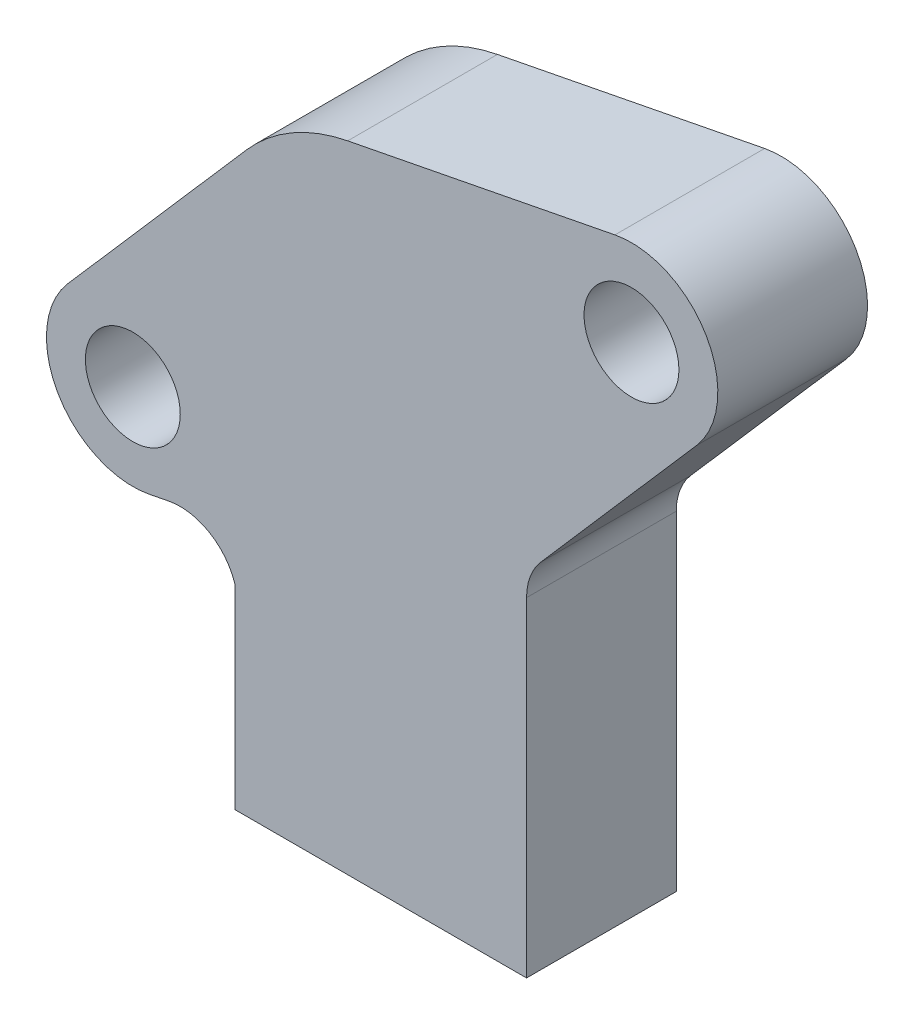
SolidWorks part; units mm, degrees
ref_plane "Front Plane" through (0, 0, 0) normal (0, 0, 1) x (1, 0, 0)
ref_plane "Top Plane" through (0, 0, 0) normal (0, 1, 0) x (1, 0, 0)
ref_plane "Right Plane" through (0, 0, 0) normal (1, 0, 0) x (0, 0, -1)
sketch "Sketch1" plane through (0, 0, 2.1073) normal (0, 0, 1) x (1, 0, 0)
  line L0 (13.3239, 2.6619) -> (0.6739, 2.6619) construction
  line L1 (0.6739, 2.6619) -> (0.6739, -2.4381) construction
  line L2 (0.6739, -2.4381) -> (13.3239, -2.4381) construction
  line L3 (13.3239, -2.4381) -> (13.3239, 2.6619) construction
  line L4 (13.6414, 2.9794) -> (0.3564, 2.9794)
  line L5 (0.3564, 2.9794) -> (0.3564, -2.7556)
  line L6 (0.3564, -2.7556) -> (13.6414, -2.7556)
  line L7 (-0.9761, 8.4284) -> (0.2939, 8.4284)
  line L8 (15.8915, 15.0877) -> (24.488, 24.9606)
  line L9 (19.9838, 32.7623) -> (5.2476, 29.8855)
  line L10 (-0.3323, 26.6639) -> (-10.1918, 15.3404)
  line L11 (-5.6875, 7.5388) -> (-4.5981, 7.7515)
  line L12 (-0.9761, 8.4284) -> (0.2939, 8.4284)
  line L13 (0.2939, 8.4284) -> (0.2939, 9.933)
  line L15 (15.8915, 15.0877) -> (24.488, 24.9606)
  line L16 (19.9838, 32.7623) -> (5.2476, 29.8855)
  line L17 (-0.3323, 26.6639) -> (-10.1918, 15.3404)
  line L18 (-5.6875, 7.5388) -> (-4.5981, 7.7515)
  line L21 (13.6414, -2.7556) -> (13.6414, 2.9794)
  line L44 (0.2939, 8.4284) -> (0.2939, 9.933)
  line L45 (-0.8698, 15.2437) -> (-0.9761, 15.4746)
  line L46 (-0.8698, 15.2437) -> (-0.9761, 15.4746)
  line L47 (15.111, 16.1833) -> (14.5824, 14.7049)
  line L48 (15.111, 16.1833) -> (14.5824, 14.7049)
  line L49 (13.841, 10.4291) -> (13.841, 8.4284)
  line L50 (13.841, 10.4291) -> (13.841, 8.4284)
  line L51 (13.841, 8.4284) -> (15.111, 8.4284)
  line L52 (13.841, 8.4284) -> (15.111, 8.4284)
  line L53 (15.111, 8.4284) -> (15.111, 13.0027)
  line L54 (15.111, 8.4284) -> (15.111, 13.0027)
  circle A0 centre (-6.6, 12.213) radius 2.6162 construction
  circle A1 centre (20.8963, 28.088) radius 2.6162 construction
  circle A2 centre (-6.6, 12.213) radius 2.6162
  circle A3 centre (20.8963, 28.088) radius 2.6162
  arc A5 (15.8915, 15.0877) -> (15.111, 13.0027) centre (18.286, 13.0027) ccw
  arc A6 (24.488, 24.9606) -> (19.9838, 32.7623) centre (20.8963, 28.088) ccw
  arc A7 (5.2476, 29.8855) -> (-0.3323, 26.6639) centre (7.1481, 20.1505) ccw
  arc A8 (-10.1918, 15.3404) -> (-5.6875, 7.5388) centre (-6.6, 12.213) ccw
  arc A9 (-0.9761, 8.4284) -> (-4.5981, 7.7515) centre (-0.9761, -1.5994) ccw
  arc A10 (15.8915, 15.0877) -> (15.111, 13.0027) centre (18.286, 13.0027) ccw
  arc A11 (24.488, 24.9606) -> (19.9838, 32.7623) centre (20.8963, 28.088) ccw
  arc A12 (5.2476, 29.8855) -> (-0.3323, 26.6639) centre (7.1481, 20.1505) ccw
  arc A13 (-10.1918, 15.3404) -> (-5.6875, 7.5388) centre (-6.6, 12.213) ccw
  arc A30 (-0.9761, 8.4284) -> (-4.5981, 7.7515) centre (-0.9761, -1.5994) ccw
  arc A31 (0.2939, 9.933) -> (-0.8698, 15.2437) centre (-12.4061, 9.933) ccw
  arc A32 (0.2939, 9.933) -> (-0.8698, 15.2437) centre (-12.4061, 9.933) ccw
  arc A33 (15.111, 16.1833) -> (-0.9761, 15.4746) centre (6.9229, 19.1109) ccw
  arc A34 (15.111, 16.1833) -> (-0.9761, 15.4746) centre (6.9229, 19.1109) ccw
  arc A35 (14.5824, 14.7049) -> (13.841, 10.4291) centre (26.541, 10.4291) ccw
  arc A36 (14.5824, 14.7049) -> (13.841, 10.4291) centre (26.541, 10.4291) ccw
  dimension "D1" = 0
  dimension "D2" = 0.3175
extrude "Boss-Extrude1" add sketch "Sketch1" along normal blind 8.255
sketch "Sketch2" plane through (0, 0, 10.3623) normal (0, 0, 1) x (1, 0, 0)
  line L0 (0.2939, 2.9794) -> (13.841, 2.9794)
  line L1 (0.6739, 2.6619) -> (13.3239, 2.6619) construction
  line L2 (-0.9761, 2.9039) -> (-0.9761, 5.6344) construction
  line L3 (-0.9761, 2.9039) -> (-0.9761, 5.6344)
  line L4 (0.2939, 8.4284) -> (0.2939, 2.9794)
  line L5 (13.841, 10.4291) -> (13.841, 8.4284)
  line L8 (-0.8698, 15.2437) -> (-0.9761, 15.4746)
  line L9 (15.111, 16.1833) -> (14.5824, 14.7049)
  line L10 (13.841, 2.9794) -> (13.841, 8.4284)
  line L13 (-0.8698, 15.2437) -> (-0.9761, 15.4746)
  line L14 (15.111, 16.1833) -> (14.5824, 14.7049)
  line L15 (15.111, 8.4284) -> (15.111, 2.9039)
  line L16 (0.2939, 2.9039) -> (0.2939, 2.9794)
  line L17 (13.841, 2.9039) -> (13.841, 2.9794)
  line L20 (0.2939, 2.9039) -> (-0.9761, 2.9039)
  line L21 (-0.9761, 2.9039) -> (-0.9761, -5.1606)
  line L22 (-0.9761, -5.1606) -> (15.111, -5.1606)
  line L23 (-5.6875, 7.5388) -> (-4.5981, 7.7515)
  line L24 (-5.6875, 7.5388) -> (-4.5981, 7.7515)
  line L25 (-0.9761, 8.4284) -> (0.2939, 8.4284)
  line L26 (-0.9761, 8.4284) -> (0.2939, 8.4284)
  line L27 (0.2939, 8.4284) -> (0.2939, 9.933)
  line L28 (0.2939, 8.4284) -> (0.2939, 9.933)
  line L29 (13.841, 8.4284) -> (15.111, 8.4284)
  line L30 (13.841, 8.4284) -> (15.111, 8.4284)
  line L31 (15.111, 8.4284) -> (15.111, 13.0027)
  line L32 (15.111, 8.4284) -> (15.111, 13.0027)
  line L33 (15.8915, 15.0877) -> (24.488, 24.9606)
  line L34 (15.8915, 15.0877) -> (24.488, 24.9606)
  line L35 (19.9838, 32.7623) -> (5.2476, 29.8855)
  line L36 (19.9838, 32.7623) -> (5.2476, 29.8855)
  line L37 (-0.3323, 26.6639) -> (-10.1918, 15.3404)
  line L38 (-0.3323, 26.6639) -> (-10.1918, 15.3404)
  line L39 (15.111, -5.1606) -> (15.111, 2.9039)
  line L40 (15.111, 2.9039) -> (13.841, 2.9039)
  line L41 (13.841, 2.9039) -> (13.841, -3.7636)
  line L42 (13.841, -3.7636) -> (0.2939, -3.7636)
  line L43 (0.2939, -3.7636) -> (0.2939, 2.9039)
  line L44 (0.2939, 2.9039) -> (-0.9761, 2.9039)
  line L45 (-0.9761, 2.9039) -> (-0.9761, -5.1606)
  line L46 (-0.9761, -5.1606) -> (15.111, -5.1606)
  line L47 (15.111, -5.1606) -> (15.111, 2.9039)
  line L48 (15.111, 2.9039) -> (13.841, 2.9039)
  line L49 (13.841, 2.9039) -> (13.841, -3.7636)
  line L50 (13.841, -3.7636) -> (0.2939, -3.7636)
  line L51 (0.2939, -3.7636) -> (0.2939, 2.9039)
  arc A0 (-0.9761, 5.6344) -> (-4.5981, 7.7515) centre (-3.9898, 4.6353) ccw construction
  arc A1 (-0.9761, 5.6344) -> (-4.5981, 7.7515) centre (-3.9898, 4.6353) ccw
  arc A3 (0.2939, 9.933) -> (-0.8698, 15.2437) centre (-12.4061, 9.933) ccw
  arc A4 (15.111, 16.1833) -> (-0.9761, 15.4746) centre (6.9229, 19.1109) ccw
  arc A5 (14.5824, 14.7049) -> (13.841, 10.4291) centre (26.541, 10.4291) ccw
  arc A6 (0.2939, 9.933) -> (-0.8698, 15.2437) centre (-12.4061, 9.933) ccw
  arc A7 (15.111, 16.1833) -> (-0.9761, 15.4746) centre (6.9229, 19.1109) ccw
  arc A8 (14.5824, 14.7049) -> (13.841, 10.4291) centre (26.541, 10.4291) ccw
  arc A14 (-0.9761, 8.4284) -> (-4.5981, 7.7515) centre (-0.9761, -1.5994) ccw
  arc A15 (-0.9761, 8.4284) -> (-4.5981, 7.7515) centre (-0.9761, -1.5994) ccw
  arc A16 (15.8915, 15.0877) -> (15.111, 13.0027) centre (18.286, 13.0027) ccw
  arc A17 (15.8915, 15.0877) -> (15.111, 13.0027) centre (18.286, 13.0027) ccw
  arc A18 (24.488, 24.9606) -> (19.9838, 32.7623) centre (20.8963, 28.088) ccw
  arc A19 (24.488, 24.9606) -> (19.9838, 32.7623) centre (20.8963, 28.088) ccw
  arc A20 (5.2476, 29.8855) -> (-0.3323, 26.6639) centre (7.1481, 20.1505) ccw
  arc A21 (5.2476, 29.8855) -> (-0.3323, 26.6639) centre (7.1481, 20.1505) ccw
  arc A22 (-10.1918, 15.3404) -> (-5.6875, 7.5388) centre (-6.6, 12.213) ccw
  arc A23 (-10.1918, 15.3404) -> (-5.6875, 7.5388) centre (-6.6, 12.213) ccw
  circle M10 centre (20.8963, 28.088) radius 2.6162
  circle M11 centre (-6.6, 12.213) radius 2.6162
  arc M14 (15.111, 13.0027) -> (15.8915, 15.0877) centre (18.286, 13.0027) cw
  line M15 (15.8915, 15.0877) -> (24.488, 24.9606)
  arc M16 (24.488, 24.9606) -> (19.9838, 32.7623) centre (20.8963, 28.088) ccw
  line M17 (19.9838, 32.7623) -> (5.2476, 29.8855)
  arc M18 (5.2476, 29.8855) -> (-0.3323, 26.6639) centre (7.1481, 20.1505) ccw
  line M19 (-0.3323, 26.6639) -> (-10.1918, 15.3404)
  arc M20 (-10.1918, 15.3404) -> (-5.6875, 7.5388) centre (-6.6, 12.213) ccw
  line M21 (-5.6875, 7.5388) -> (-4.5981, 7.7515)
  line M24 (13.841, 10.4291) -> (13.841, 8.4284)
  arc M27 (0.2939, 9.933) -> (-0.8698, 15.2437) centre (-12.4061, 9.933) ccw
  line M28 (-0.8698, 15.2437) -> (-0.9761, 15.4746)
  arc M29 (-0.9761, 15.4746) -> (15.111, 16.1833) centre (6.9229, 19.1109) cw
  line M30 (15.111, 16.1833) -> (14.5824, 14.7049)
  arc M31 (14.5824, 14.7049) -> (13.841, 10.4291) centre (26.541, 10.4291) ccw
  arc M32 (-4.5981, 7.7515) -> (-0.9761, 8.4284) centre (-0.9761, -1.5994) cw
  line M33 (-0.9761, 8.4284) -> (0.2939, 8.4284)
  line M34 (0.2939, 8.4284) -> (0.2939, 9.933)
  line M35 (13.841, 8.4284) -> (15.111, 8.4284)
  line M36 (15.111, 8.4284) -> (15.111, 13.0027)
  dimension "D2" = 0.3175
  dimension "D1" = 0
  dimension "D3" = 0
extrude "Boss-Extrude2" add sketch "Sketch2" against normal up to surface (8.255 mm away) contours M20 M21 M32 M33 M34 M27 M28 M29 M30 M31 M24 M35 M36 M14 M15 M16 M17 M18 M19 M11 M10 | L50 L51 L44 L45 L46 L47 L48 L49 | A1 L3 L44 L51 L50 L49 L48 L15 L10 L0 L4 M35 M33 M32 | L0 L10 L4 M24 M31 M30 M29 M28 M27 M34 | L48 L15 L10 L17 M35
sketch "Sketch3" plane through (0, -5.1606, 0) normal (0, -1, 0) x (1, 0, 0)
  line L0 (-0.9761, 10.3623) -> (15.111, 10.3623) construction
  line L1 (15.111, 2.1073) -> (-0.9761, 2.1073) construction
  line L3 (2.94, 9.0923) -> (11.195, 9.0923)
  line L4 (2.94, 9.0923) -> (2.94, -4.8777)
  line L5 (2.94, -4.8777) -> (11.195, -4.8777)
  line L6 (11.195, 9.0923) -> (11.195, -4.8777)
  line L7 (2.94, 9.0923) -> (11.195, -4.8777) construction
  line L8 (2.94, -4.8777) -> (11.195, 9.0923) construction
  line L9 (15.111, 2.1073) -> (-0.9761, 2.1073)
  point P0 (7.0675, 2.1073)
  point P9 (0, 0)
  point P10 (0, 0)
  point P11 (0, 0)
  dimension "D2" = 1.27
  dimension "D1" = 8.255
extrude "Cut-Extrude1" cut sketch "Sketch3" against normal up to surface (1.397 mm away) and the other way through all contours L9 L6 L3 L4 up to face at (7.0675, -3.7636, 6.2348)
sketch "Sketch4" plane through (0, 0, 10.3623) normal (0, 0, 1) x (1, 0, 0)
  line L4 (13.841, 2.9039) -> (13.841, 2.9794)
  line L5 (13.841, 2.9039) -> (13.841, 2.9794)
  line L44 (13.841, -3.7636) -> (13.841, 2.9039)
  line L45 (13.841, -3.7636) -> (13.841, 2.9039)
  line L46 (0.2939, -3.7636) -> (13.841, -3.7636)
  line L47 (0.2939, -3.7636) -> (13.841, -3.7636)
  line L48 (0.2939, 2.9039) -> (0.2939, -3.7636)
  line L49 (0.2939, 2.9039) -> (0.2939, -3.7636)
  line L50 (0.2939, 2.9794) -> (0.2939, 2.9039)
  line L51 (0.2939, 2.9794) -> (0.2939, 2.9039)
  line L52 (13.841, 2.9794) -> (0.2939, 2.9794)
  line L53 (13.841, 2.9794) -> (0.2939, 2.9794)
  dimension "D1" = 0
extrude "Boss-Extrude3" add sketch "Sketch4" against normal up to surface (1.27 mm away) up to face at (7.0675, -4.4621, 9.0923)
